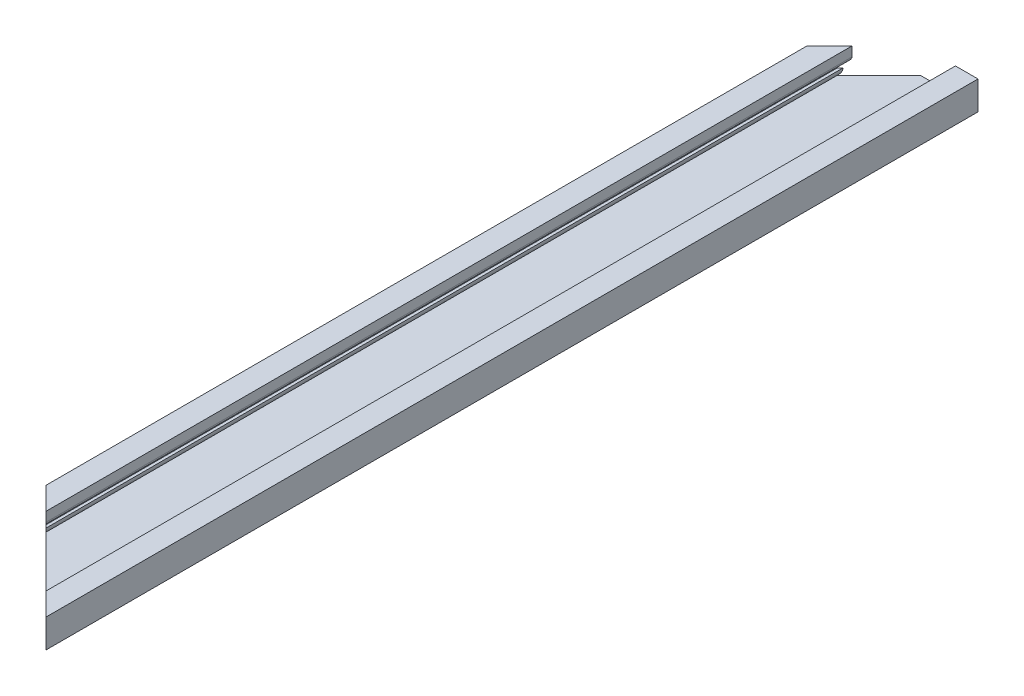
SolidWorks part; units mm, degrees
ref_plane "정면" through (0, 0, 0) normal (0, 0, 1) x (1, 0, 0)
ref_plane "윗면" through (0, 0, 0) normal (0, 1, 0) x (1, 0, 0)
ref_plane "우측면" through (0, 0, 0) normal (1, 0, 0) x (0, 0, -1)
sketch "스케치1" plane through (0, 0, 0) normal (0, 0, 1) x (1, 0, 0)
  line L1 (-30, 7.5) -> (30, 7.5)
  line L2 (-30, 7.5) -> (-30, -7.5)
  line L3 (-30, -7.5) -> (30, -7.5)
  line L4 (30, 7.5) -> (30, -7.5)
  line L5 (-30, 7.5) -> (30, -7.5) construction
  line L6 (-30, -7.5) -> (30, 7.5) construction
  point P0 (0, 0)
  dimension "D1" = 60
  dimension "D2" = 15
extrude "보스-돌출1" add sketch "스케치1" along normal blind 520
sketch "스케치2" plane through (0, 0, 0) normal (0, 0, -1) x (-1, 0, 0)
  line L0 (30, -7.5) -> (-30, -7.5) construction
  line L2 (-30, -7.5) -> (-30, 7.5) construction
  line L3 (30, 7.5) -> (30, -7.5) construction
  circle A0 centre (-25, -2.5) radius 3
  circle A1 centre (25, -2.5) radius 3
  dimension "D1" = 6
  dimension "D3" = 5
  dimension "D4" = 6
  dimension "D6" = 5
  dimension "D2" = 5
  dimension "D5" = 5
extrude "컷-돌출1" cut sketch "스케치2" against normal through all
sketch "스케치3" plane through (0, 0, 0) normal (0, 0, -1) x (-1, 0, 0)
  line L0 (-22.1716, -6) -> (22.1716, -6)
  line L1 (-20.5, -2.5) -> (-25, -2.5)
  line L2 (-25, -2.5) -> (-25, 0.5)
  line L3 (-25, 0.5) -> (25, 0.5)
  line L4 (25, 0.5) -> (25, -2.5)
  line L5 (25, -2.5) -> (20.5, -2.5)
  line L6 (30, -7.5) -> (-30, -7.5) construction
  arc A0 (22.1716, -6) -> (20.5, -2.5) centre (25, -2.5) cw
  arc A1 (-22.1716, -6) -> (-20.5, -2.5) centre (-25, -2.5) ccw
  circle A2 centre (-25, -2.5) radius 3 construction
  circle A3 centre (25, -2.5) radius 3 construction
  dimension "D2" = 1.5
  dimension "D1" = 1.5
  dimension "1.5" = 1.5
extrude "컷-돌출2" cut sketch "스케치3" against normal through all
sketch "스케치4" plane through (0, 0, 0) normal (0, 0, -1) x (-1, 0, 0)
  line L0 (-18.1431, 0.5) -> (18.1569, 0.5)
  line L1 (25, 0.5) -> (-25, 0.5) construction
  line L2 (-18.1431, 0.5) -> (-18.1431, 7.5)
  line L3 (-30, 7.5) -> (30, 7.5) construction
  line L4 (-18.1431, 7.5) -> (18.1569, 7.5)
  line L5 (18.1569, 7.5) -> (18.1569, 0.5)
  point P5 (0, 0)
  dimension "D1" = 36.3
extrude "컷-돌출3" cut sketch "스케치4" against normal through all
fillet "필렛1" radius 2 2 edges at (-18.1569, 0.5, 260) (18.1431, 0.5, 260)
sketch "스케치5" plane through (0, -7.5, 0) normal (0, -1, 0) x (1, 0, 0)
  line L0 (-30, 520) -> (-30, 460)
  line L1 (-30, 520) -> (-30, 0) construction
  line L2 (-30, 460) -> (30, 520)
  line L5 (-30, 0) -> (30, 0)
  line L6 (-30, 260) -> (30, 260) construction
  line L7 (30, 520) -> (30, 0) construction
  line L15 (-30, 520) -> (30, 520)
  line L17 (-30, 60) -> (30, 0)
  line L18 (-30, 0) -> (-30, 60)
  point P5 (0, 530)
  point P7 (30, 530)
  point P15 (0, 530)
  point P16 (0, 530)
  point P17 (0, 530)
  dimension "D1" = 45
extrude "컷-돌출4" cut sketch "스케치5" against normal through all
sketch "스케치7" plane through (0, -7.5, 0) normal (0, -1, 0) x (1, 0, 0)
  line L1 (30, 0) -> (0, 0)
  line L2 (30, 0) -> (30, 30)
  line L3 (30, 30) -> (0, 30)
  line L4 (0, 0) -> (0, 30)
  dimension "D1" = 30
  dimension "D2" = 30
extrude "컷-돌출6" cut sketch "스케치7" against normal through all and the other way through all
